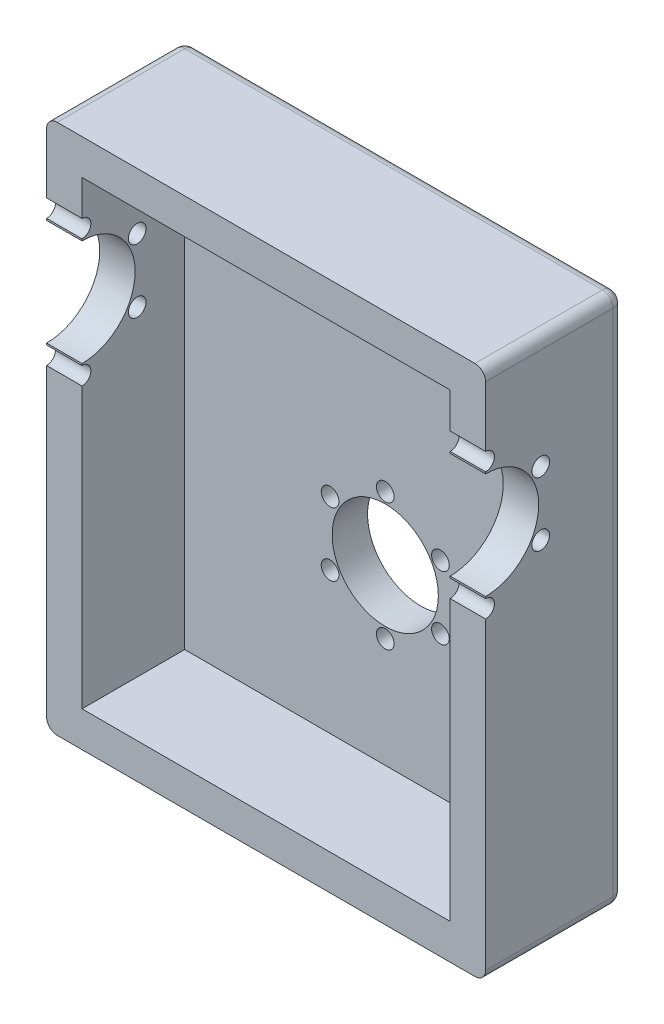
SolidWorks part; units mm, degrees
ref_plane "Front Plane" through (0, 0, 0) normal (0, 0, 1) x (1, 0, 0)
ref_plane "Top Plane" through (0, 0, 0) normal (0, 1, 0) x (1, 0, 0)
ref_plane "Right Plane" through (0, 0, 0) normal (1, 0, 0) x (0, 0, -1)
sketch "Sketch1" plane through (0, 0, 0) normal (0, 0, 1) x (1, 0, 0)
  line L0 (62, 75) -> (-62, 75)
  line L1 (52, 65) -> (-52, 65)
  line L2 (52, 65) -> (52, -65)
  line L3 (52, -65) -> (-52, -65)
  line L4 (-52, 65) -> (-52, -65)
  line L5 (52, 65) -> (-52, -65) construction
  line L6 (52, -65) -> (-52, 65) construction
  line L7 (-62, 75) -> (-62, -75)
  line L8 (62, -75) -> (-62, -75)
  line L9 (62, 75) -> (62, -75)
  point P0 (0, 0)
  dimension "D1" = 104
  dimension "D2" = 130
  dimension "D3" = 10
extrude "Boss-Extrude1" add sketch "Sketch1" along normal blind 29
sketch "Sketch2" plane through (0, 0, 0) normal (0, 0, -1) x (-1, 0, 0)
  line L0 (62, 75) -> (62, -75) construction
  line L1 (62, -75) -> (-62, -75) construction
  line L2 (-62, -75) -> (-62, 75) construction
  line L3 (-62, 75) -> (62, 75) construction
  line L4 (62, 75) -> (62, -75)
  line L5 (62, -75) -> (-62, -75)
  line L6 (-62, -75) -> (-62, 75)
  line L7 (-62, 75) -> (62, 75)
extrude "Boss-Extrude2" add sketch "Sketch2" along normal blind 10
sketch "Sketch3" plane through (0, 0, -10) normal (0, 0, -1) x (-1, 0, 0)
  line L0 (-62, 75) -> (-62, -75) construction
  line L1 (-62, -75) -> (62, -75) construction
  circle A0 centre (-4.66, -16.02) radius 15
  circle A1 centre (-4.66, -16.02) radius 18 construction
  circle A2 centre (-4.66, 1.98) radius 2.5
  circle A3 centre (10.9285, -7.02) radius 2.5
  circle A4 centre (10.9285, -25.02) radius 2.5
  circle A5 centre (-4.66, -34.02) radius 2.5
  circle A6 centre (-20.2485, -25.02) radius 2.5
  circle A7 centre (-20.2485, -7.02) radius 2.5
  point P22 (-4.66, -16.02)
  dimension "D1" = 30
  dimension "D4" = 36
  dimension "D5" = 5
  dimension "D2" = 57.34
  dimension "D3" = 58.98
  dimension "D6" = 6
extrude "Cut-Extrude1" cut sketch "Sketch3" against normal through all both and the other way through all
sketch "Sketch4" plane through (-62, 0, 0) normal (-1, 0, 0) x (0, 0, 1)
  line L0 (29, 75) -> (29, -75) construction
  line L1 (29, 75) -> (-10, 75) construction
  circle A0 centre (29, 34.48) radius 15
  circle A1 centre (29, 34.48) radius 18 construction
  circle A2 centre (29, 52.48) radius 2.5
  circle A3 centre (44.5885, 43.48) radius 2.5
  circle A4 centre (44.5885, 25.48) radius 2.5
  circle A5 centre (29, 16.48) radius 2.5
  circle A6 centre (13.4115, 25.48) radius 2.5
  circle A7 centre (13.4115, 43.48) radius 2.5
  point P21 (29, 34.48)
  dimension "D1" = 30
  dimension "D3" = 36
  dimension "D4" = 5
  dimension "D2" = 40.52
  dimension "D5" = 6
extrude "Cut-Extrude2" cut sketch "Sketch4" against normal through all both and the other way through all
fillet "Fillet1" radius 3 8 edges at (-62, -75, 9.5) (0, -75, -10) (62, -75, 9.5) (62, 0, -10) (-62, 0, -10) (-62, 75, 9.5) (62, 75, 9.5) (0, 75, -10)
